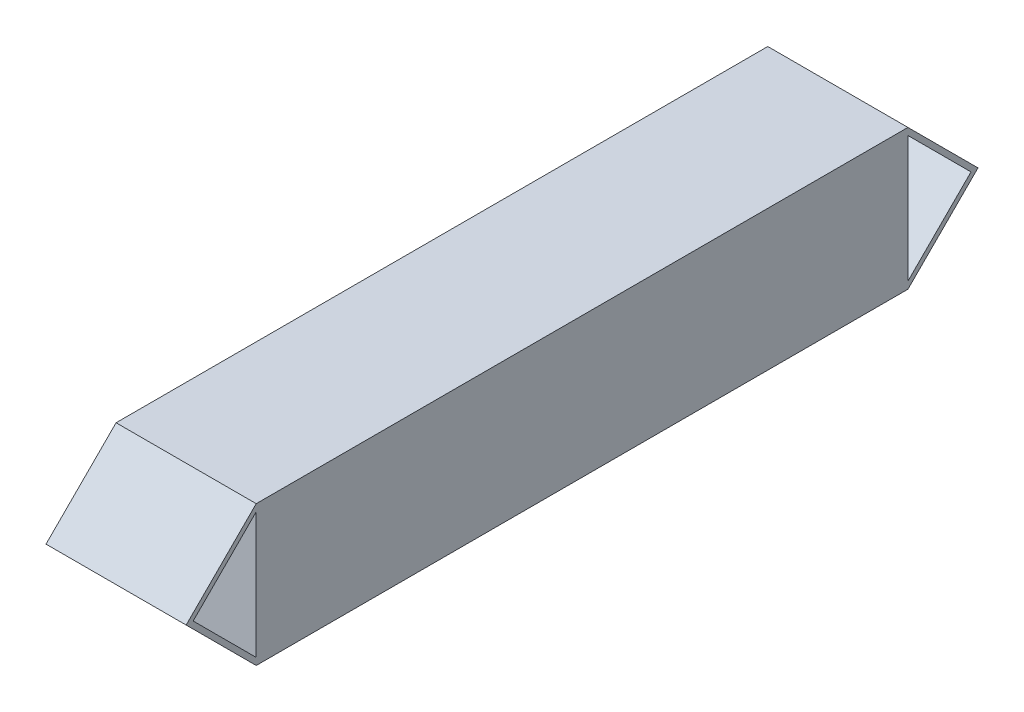
SolidWorks part; units mm, degrees
ref_plane "Alzado" through (0, 0, 0) normal (0, 0, 1) x (1, 0, 0)
ref_plane "Planta" through (0, 0, 0) normal (0, 1, 0) x (1, 0, 0)
ref_plane "Vista lateral" through (0, 0, 0) normal (1, 0, 0) x (0, 0, -1)
sketch "Croquis1" plane through (0, 0, 0) normal (0, 0, 1) x (1, 0, 0)
  line L1 (-20, -20) -> (20, -20)
  line L2 (-20, -20) -> (-20, 20)
  line L3 (-20, 20) -> (20, 20)
  line L4 (20, -20) -> (20, 20)
  line L5 (-20, -20) -> (20, 20) construction
  line L6 (-20, 20) -> (20, -20) construction
  point P0 (0, 0)
  dimension "D1" = 40
  dimension "D2" = 40
extrude "Saliente-Extruir1" add sketch "Croquis1" along normal blind 186
sketch "Croquis4" plane through (20, 0, 0) normal (1, 0, 0) x (0, 0, -1)
  line L0 (0, 20) -> (0, -20)
  line L1 (0, 0) -> (20, 0)
  line L2 (20, 0) -> (0, 20)
  line L3 (20, 0) -> (0, -20)
  line L4 (0, 20) -> (0, 18)
  line L5 (20, 0) -> (18, 0)
  line L6 (0, -20) -> (0, -18)
  line L7 (0, 18) -> (18, 0)
  line L8 (0, -18) -> (18, 0)
  line L9 (0, 20) -> (-186, 20)
  line L10 (0, -20) -> (-186, -20)
  line L11 (-93, 20) -> (-93, -20)
  line L12 (-186, -18) -> (-204, 0)
  line L13 (-186, 18) -> (-204, 0)
  line L14 (-186, -20) -> (-186, -18)
  line L15 (-206, 0) -> (-204, 0)
  line L16 (-186, 20) -> (-186, 18)
  line L17 (-206, 0) -> (-186, -20)
  line L18 (-206, 0) -> (-186, 20)
  line L19 (-186, 0) -> (-206, 0)
  line L20 (-186, 20) -> (-186, -20)
  line M4 (0, -20) -> (0, 20)
  line M6 (-186, 20) -> (-186, -20)
  dimension "D1" = 20
  dimension "D2" = 2
  dimension "D3" = 2
extrude "Saliente-Extruir2" add sketch "Croquis4" against normal blind 40 contours L8 L3 L1 M4 | L7 L1 L2 M4 | L18 L15 L13 M6 | L15 L17 L12 M6
